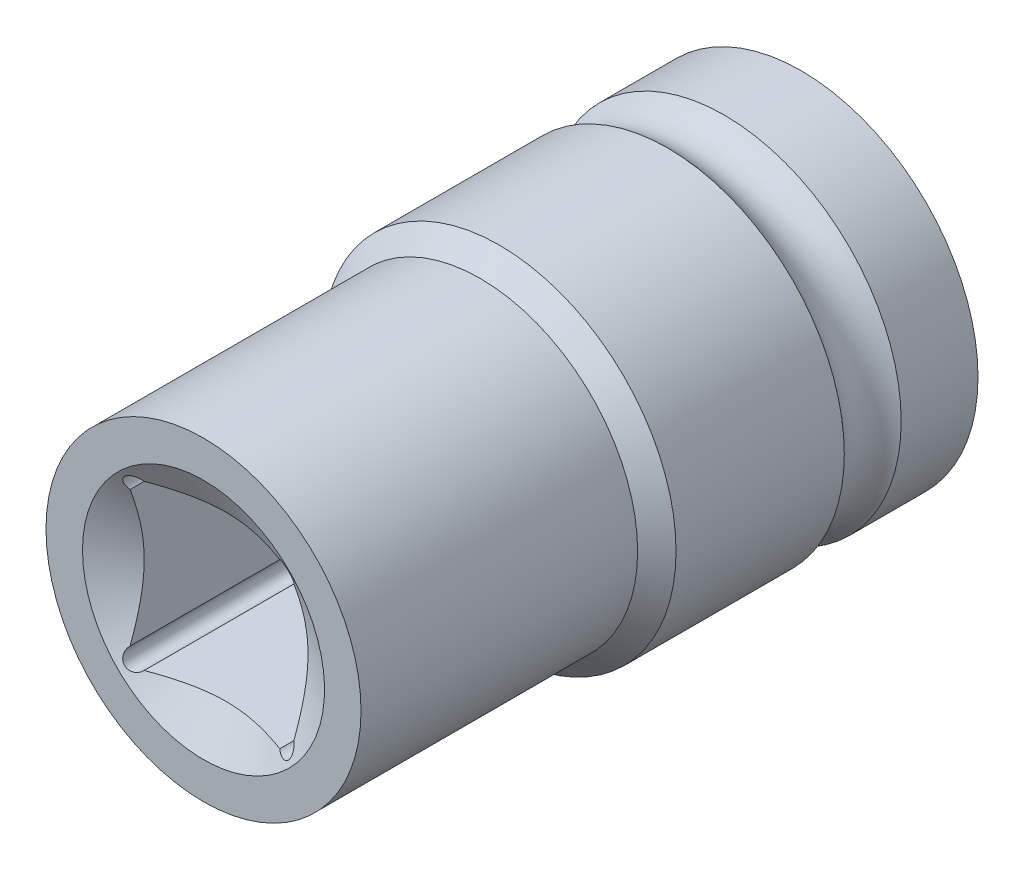
SolidWorks part; units mm, degrees
material "Cast Alloy Steel"
ref_plane "Front Plane" through (0, 0, 0) normal (0, 0, 1) x (1, 0, 0)
ref_plane "Top Plane" through (0, 0, 0) normal (0, 1, 0) x (1, 0, 0)
ref_plane "Right Plane" through (0, 0, 0) normal (1, 0, 0) x (0, 0, -1)
sketch "Sketch1" plane through (0, 0, 0) normal (1, 0, 0) x (0, 0, -1)
  line L0 (0, 20.5) -> (0, 15.75)
  line L1 (0, 20.5) -> (36, 20.5)
  line L2 (36, 20.5) -> (38.5, 23)
  line L3 (38.5, 23) -> (60.4, 23)
  line L4 (67.8, 23) -> (77.8, 23)
  line L5 (77.8, 23) -> (77.8, 19)
  line L6 (66.8303, 0) -> (9.0933, 0)
  line L7 (0, 0) -> (-20.5315, 0) construction
  line L8 (77.8, 19) -> (66.8303, 0)
  line L9 (64.1, 21.2) -> (64.1, 0) construction
  line L10 (0, 15.75) -> (9.0933, 0)
  arc A0 (60.4, 23) -> (67.8, 23) centre (64.1, 25.9028) ccw
  dimension "D2" = 46
  dimension "D3" = 41
  dimension "D4" = 36
  dimension "D5" = 38
  dimension "D6" = 45
  dimension "D7" = 7.4
  dimension "D8" = 30
  dimension "D9" = 10
  dimension "D10" = 42.4
  dimension "D11" = 30
  dimension "D12" = 31.5
  dimension "D13" = 77.8
revolve "Revolve1" add sketch "Sketch1" angle 360 about L7
sketch "Sketch2" plane through (0, 0, 0) normal (0, 0, 1) x (1, 0, 0)
  line L0 (-10.66, 8.8215) -> (-10.66, -8.8215)
  line L1 (-8.8215, 10.66) -> (8.8215, 10.66)
  line L2 (-8.8215, -10.66) -> (8.8215, -10.66)
  line L3 (10.66, 8.8215) -> (10.66, -8.8215)
  line L4 (-10.66, 10.66) -> (10.66, -10.66) construction
  line L5 (-10.66, -10.66) -> (10.66, 10.66) construction
  arc A0 (-8.8215, 10.66) -> (-10.66, 8.8215) centre (-9.7408, 9.7408) ccw
  arc A1 (10.66, 8.8215) -> (8.8215, 10.66) centre (9.7408, 9.7408) ccw
  arc A2 (8.8215, -10.66) -> (10.66, -8.8215) centre (9.7408, -9.7408) ccw
  arc A3 (-10.66, -8.8215) -> (-8.8215, -10.66) centre (-9.7408, -9.7408) ccw
  point P1 (0, 0)
  dimension "D2" = 2.6
  dimension "D1" = 21.32
extrude "Cut-Extrude1" cut sketch "Sketch2" against normal blind 30
sketch "Sketch3" plane through (0, 0, -30) normal (0, 0, 1) x (1, 0, 0)
  circle A0 centre (0, 0) radius 10
  dimension "D1" = 20
extrude "Cut-Extrude2" cut sketch "Sketch3" against normal blind 30
sketch "Sketch4" plane through (0, 0, -77.8) normal (0, 0, -1) x (-1, 0, 0)
  line L0 (-12.85, -9.668) -> (-12.85, 9.668)
  line L1 (-9.668, -12.85) -> (9.668, -12.85)
  line L2 (-9.668, 12.85) -> (9.668, 12.85)
  line L3 (12.85, -9.668) -> (12.85, 9.668)
  line L4 (-12.85, -12.85) -> (12.85, 12.85) construction
  line L5 (-12.85, 12.85) -> (12.85, -12.85) construction
  arc A0 (-12.85, 9.668) -> (-9.668, 12.85) centre (-11.259, 11.259) cw
  arc A1 (9.668, 12.85) -> (12.85, 9.668) centre (11.259, 11.259) cw
  arc A2 (9.668, -12.85) -> (12.85, -9.668) centre (11.259, -11.259) ccw
  arc A3 (-12.85, -9.668) -> (-9.668, -12.85) centre (-11.259, -11.259) ccw
  point P1 (0, 0)
  dimension "D1" = 2.25
  dimension "D2" = 25.7
extrude "Cut-Extrude3" cut sketch "Sketch4" against normal blind 31.3
